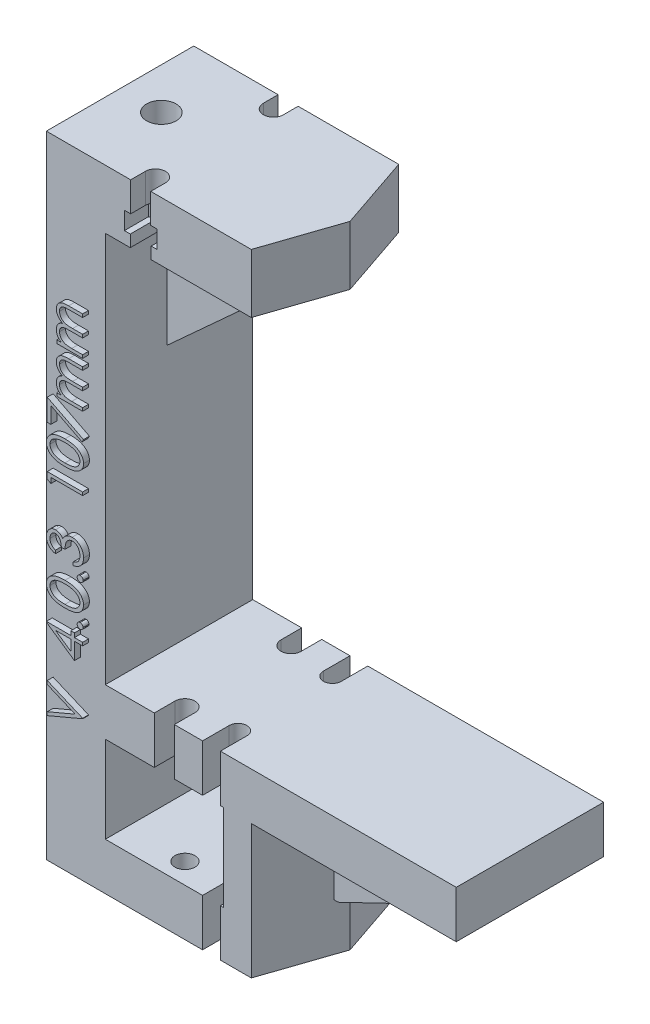
SolidWorks part; units mm, degrees
material "ABS"
ref_plane "Front" through (0, 0, 0) normal (0, 0, 1) x (1, 0, 0)
ref_plane "Top" through (0, 0, 0) normal (0, 1, 0) x (1, 0, 0)
ref_plane "Right" through (0, 0, 0) normal (1, 0, 0) x (0, 0, -1)
sketch "Sketch6" plane through (0, 0, 0) normal (0, 0, 1) x (1, 0, 0)
  line L0 (-25, 53.5) -> (15, 53.5)
  line L1 (15, 53.5) -> (15, 45.5)
  line L2 (15, 45.5) -> (-15, 45.5)
  line L3 (-15, 45.5) -> (-15, -45.5)
  line L4 (-15, -45.5) -> (25, -45.5)
  line L5 (25, -45.5) -> (25, -53.5)
  line L6 (25, -53.5) -> (-25, -53.5)
  line L7 (-25, -53.5) -> (-25, 53.5)
  line L8 (-25, 53.5) -> (25, -53.5) construction
  dimension "D1" = 107
  dimension "D2" = 8
  dimension "D4" = 50
  dimension "D5" = 40
extrude "Boss-Extrude2" add sketch "Sketch6" along normal mid plane 25
sketch "Sketch15" plane through (0, 0, 12.5) normal (0, 0, 1) x (1, 0, 0)
  line L0 (-15, -22.805) -> (15, -22.805)
  line L1 (-15, -45.5) -> (-15, 45.5) construction
  line L2 (-15, -30.805) -> (5, -30.805)
  line L3 (5, -53.5) -> (15, -53.5)
  line L4 (15, -53.5) -> (15, -22.805)
  line L5 (-25, -53.5) -> (25, -53.5) construction
  line L6 (-15, -30.805) -> (-15, -22.805)
  line L7 (5, -53.5) -> (5, -30.805)
  dimension "D2" = 8
extrude "Boss-Extrude3" add sketch "Sketch15" against normal up to surface (25 mm away) up to face at (0, 0, -12.5)
sketch "Sketch20" plane through (0, 53.5, 0) normal (0, 1, 0) x (1, 0, 0)
  line L0 (-10.7, 12.5) -> (-10.7, 10)
  line L1 (15, 12.5) -> (-25, 12.5) construction
  line L2 (-7.3, 10) -> (-7.3, 12.5)
  line L3 (-7.3, 12.5) -> (-10.7, 12.5)
  line L4 (0, 0) -> (15, 0) construction
  line L5 (15, -12.5) -> (15, 12.5) construction
  line L6 (-7.3, -12.5) -> (-10.7, -12.5)
  line L7 (-7.3, -10) -> (-7.3, -12.5)
  line L8 (-10.7, -12.5) -> (-10.7, -10)
  line L9 (-9, -10) -> (-9, 10) construction
  arc A0 (-10.7, 10) -> (-7.3, 10) centre (-9, 10) ccw
  arc A1 (-10.7, -10) -> (-7.3, -10) centre (-9, -10) cw
  dimension "D1" = 1.7
  dimension "D2" = 20
extrude "Cut-Extrude2" cut sketch "Sketch20" against normal up to next
sketch "Sketch21" plane through (0, -53.5, 0) normal (0, -1, 0) x (1, 0, 0)
  line L0 (-6.7, 12.5) -> (-6.7, 9)
  line L1 (-25, 12.5) -> (25, 12.5) construction
  line L2 (-3.3, 9) -> (-3.3, 12.5)
  line L3 (-3.3, 12.5) -> (-6.7, 12.5) construction
  line L4 (-5, -9) -> (-5, 9) construction
  line L5 (-6.7, 12.5) -> (-3.3, 12.5)
  line L7 (-3.3, -12.5) -> (-6.7, -12.5)
  line L8 (-3.3, -9) -> (-3.3, -12.5)
  line L9 (-6.7, -12.5) -> (-6.7, -9)
  arc A0 (-6.7, 9) -> (-3.3, 9) centre (-5, 9) ccw
  arc A1 (-6.7, -9) -> (-3.3, -9) centre (-5, -9) cw
  dimension "D1" = 1.7
  dimension "D2" = 18
extrude "Cut-Extrude3" cut sketch "Sketch21" against normal up to surface (30.695 mm away) up to face at (0, -22.805, 0)
sketch "Sketch22" plane through (0, 0, 0) normal (0, 0, 1) x (1, 0, 0)
  line L0 (-15, 21.805) -> (11, 45.5)
  line L1 (-7.3, 45.5) -> (15, 45.5) construction
  line L2 (-15, 45.5) -> (11, 45.5)
  line L5 (-15, -22.805) -> (-15, 45.5) construction
  line L7 (-15, 45.5) -> (-10.7, 45.5) construction
  line L8 (-15, 45.5) -> (-15, 21.805)
extrude "Boss-Extrude5" add sketch "Sketch22" along normal mid plane 4
sketch "Sketch23" plane through (0, 53.5, 0) normal (0, 1, 0) x (1, 0, 0)
  line L0 (-2.51, 12.5) -> (-2.51, 9)
  line L1 (15, 12.5) -> (-7.3, 12.5) construction
  line L2 (0.51, 9) -> (0.51, 12.5)
  line L3 (0.51, 12.5) -> (-2.51, 12.5)
  line L4 (-9, 10) -> (-1, 10) construction
  line L5 (-1, 10) -> (-1, 9) construction
  line L6 (0, 0) -> (12, 0) construction
  line L8 (0.51, -12.5) -> (-2.51, -12.5)
  line L9 (0.51, -9) -> (0.51, -12.5)
  line L10 (-2.51, -12.5) -> (-2.51, -9)
  line L11 (15, -12.5) -> (15, 12.5) construction
  arc A0 (-2.51, 9) -> (0.51, 9) centre (-1, 9) ccw
  arc A1 (-2.51, -9) -> (0.51, -9) centre (-1, -9) cw
  dimension "D1" = 1.51
  dimension "D2" = 8
  dimension "D3" = 1
  dimension "D4" = 3
extrude "Cut-Extrude4" [suppressed] cut sketch "Sketch23" against normal up to next
sketch "Sketch24" plane through (0, -53.5, 0) normal (0, -1, 0) x (1, 0, 0)
  line L0 (1.49, -12.5) -> (1.49, -8)
  line L1 (-3.3, -12.5) -> (25, -12.5) construction
  line L2 (4.51, -8) -> (4.51, -12.5)
  line L3 (4.51, -12.5) -> (1.49, -12.5)
  line L4 (3, -8) -> (3, -9) construction
  line L5 (3, -9) -> (-5, -9) construction
  line L9 (4.51, 12.5) -> (1.49, 12.5)
  line L10 (4.51, 8) -> (4.51, 12.5)
  line L11 (1.49, 12.5) -> (1.49, 8)
  arc A0 (1.49, -8) -> (4.51, -8) centre (3, -8) cw
  arc A1 (1.49, 8) -> (4.51, 8) centre (3, 8) ccw
  dimension "D2" = 8
  dimension "D3" = 1
extrude "Cut-Extrude6" cut sketch "Sketch24" against normal up to surface (30.695 mm away) up to face at (-3.3333, -22.805, 0)
sketch "Sketch28" plane through (0, 53.5, 0) normal (0, 1, 0) x (1, 0, 0)
  line L0 (-10.7, 10) -> (-7.3, 10) construction
  line L1 (-10.7, -10) -> (-7.3, -10) construction
  line L2 (-7.3, -12.5) -> (-7.3, -10) construction
  arc A0 (-10.7, 10) -> (-7.3, 10) centre (-9, 10) ccw construction
  arc A1 (-7.3, -10) -> (-10.7, -10) centre (-9, -10) ccw construction
sketch "Sketch29" plane through (-25, 0, 0) normal (-1, 0, 0) x (0, 0, 1)
  line L0 (-12.5, 53.5) -> (12.5, 53.5)
  line L1 (12.5, 53.5) -> (12.5, -53.5)
  line L2 (12.5, -53.5) -> (-12.9424, -53.5)
  line L3 (-12.9424, -53.5) -> (-12.5, 53.5)
extrude "Cut-Extrude7" [suppressed] cut sketch "Sketch29" against normal blind 6
sketch "Sketch30" plane through (0, -45.5, 0) normal (0, 1, 0) x (1, 0, 0)
  line L0 (25, 12.5) -> (25, -12.5)
  line L1 (25, -12.5) -> (15, -12.5)
  line L2 (15, -12.5) -> (15, 12.5)
  line L3 (15, 12.5) -> (25, 12.5)
extrude "Cut-Extrude8" cut sketch "Sketch30" against normal up to surface (8 mm away) up to face at (-0.8, -53.5, 0)
sketch "Sketch34" plane through (0, -22.805, 0) normal (0, 1, 0) x (1, 0, 0)
  line L1 (9.755, 12.5) -> (14, 0)
  line L2 (15, -12.5) -> (4.51, -12.5) construction
  line L3 (9.755, -12.5) -> (15, -12.5)
  line L6 (15, 12.5) -> (9.755, 12.5)
  line L7 (15, 12.5) -> (4.51, 12.5) construction
  line L9 (15, -12.5) -> (15, 12.5)
  line L10 (15, 0) -> (14, 0) construction
  line L11 (14, 0) -> (9.755, -12.5)
extrude "Cut-Extrude9" cut sketch "Sketch34" against normal through all both and the other way through all
sketch "Sketch35" plane through (0, 0, 12.5) normal (0, 0, 1) x (1, 0, 0)
  line L0 (-17.85, 53.5) -> (-17.85, -53.5) construction
  line L1 (-10.7, 53.5) -> (-25, 53.5) construction
  line L2 (-25, -53.5) -> (-6.7, -53.5) construction
  text T0 "V  4.0.3  107mm" font "Century Gothic" height 6
extrude "Boss-Extrude6" add sketch "Sketch35" along normal blind 1
sketch3d "3DSketch1"
  line L0 (4.51, -22.805, 12.5) -> (4.51, -30.805, 12.5)
  line L1 (4.51, -30.805, 12.5) -> (4.51, -30.805, -12.5)
  line L2 (4.51, -30.805, -12.5) -> (4.51, -22.805, -12.5)
  line L3 (4.51, -22.805, -12.5) -> (4.51, -22.805, 12.5)
extrude "Boss-Extrude7" add sketch "3DSketch1" along direction (1, 0, 0) on the side against the normal blind 40
sketch "Sketch37" plane through (0, 0, 0) normal (0, 0, 1) x (1, 0, 0)
  line L1 (14, -30.805) -> (44.51, -30.805)
  line L3 (5, -45.5) -> (14, -45.5) construction
  line L4 (14, -30.805) -> (14, -45.5)
  line L5 (14, -45.5) -> (44.51, -30.805)
extrude "Boss-Extrude17" add sketch "Sketch37" along direction (0, 0, 1) on the side of the normal mid plane 4 separate body
sketch "Sketch38" plane through (0, 45.5, 0) normal (0, -1, 0) x (1, 0, 0)
  line L0 (-11.75, 11.5877) -> (-11.75, 12.5) construction
  line L1 (-10.7, 10) -> (-7.3, 10) construction
  line L2 (-6.25, 8.4123) -> (-6.25, 11.5877) construction
  line L3 (-9, 6.8246) -> (-6.25, 8.4123)
  line L4 (-11.75, 8.4123) -> (-9, 6.8246)
  line L5 (-11.75, 11.5877) -> (-11.75, 8.4123) construction
  line L6 (-9, 13.1754) -> (-11.75, 11.5877) construction
  line L7 (-6.25, 11.5877) -> (-9, 13.1754) construction
  line L8 (-10.7, -10) -> (-7.3, -10) construction
  line L9 (-6.25, -11.5877) -> (-6.25, -8.4123) construction
  line L10 (-6.25, -8.4123) -> (-9, -6.8246)
  line L11 (-9, -6.8246) -> (-11.75, -8.4123)
  line L12 (-11.75, -8.4123) -> (-11.75, -11.5877) construction
  line L13 (-11.75, -11.5877) -> (-9, -13.1754) construction
  line L14 (-9, -13.1754) -> (-6.25, -11.5877) construction
  line L15 (-15, 12.5) -> (-10.7, 12.5) construction
  line L17 (-7.3, 12.5) -> (9.755, 12.5) construction
  line L18 (-6.25, 12.5) -> (-6.25, 11.5877) construction
  line L19 (-11.75, -11.5877) -> (-11.75, -12.5) construction
  line L20 (-15, -12.5) -> (-10.7, -12.5) construction
  line L21 (-11.77, -12.5) -> (-6.23, -12.5)
  line L22 (-7.3, -12.5) -> (9.755, -12.5) construction
  line L23 (-6.25, -12.5) -> (-6.25, -11.5877) construction
  line L24 (-11.77, 12.5) -> (-11.77, 8.4238)
  line L25 (-11.77, 8.4238) -> (-11.75, 8.4123)
  line L26 (-6.23, 12.5) -> (-6.23, 8.4238)
  line L27 (-6.23, 8.4238) -> (-6.25, 8.4123)
  line L28 (-11.77, 12.5) -> (-6.23, 12.5)
  line L29 (-6.25, -8.4123) -> (-6.23, -8.4238)
  line L30 (-6.23, -8.4238) -> (-6.23, -12.5)
  line L31 (-11.77, -12.5) -> (-11.77, -8.4238)
  line L32 (-11.77, -8.4238) -> (-11.75, -8.4123)
  circle A1 centre (-9, 10) radius 2.75 construction
  circle A2 centre (-9, 10) radius 3.1754 construction
  circle A3 centre (-9, -10) radius 3.1754 construction
  circle A4 centre (-9, -10) radius 2.75 construction
  point P18 (-6.25, -10)
  point P19 (-9, 10)
  point P24 (-7.625, -7.6184)
  point P25 (-10.375, -7.6184)
  point P42 (-11.75, 12.0439)
  dimension "D1" = 5.5
  dimension "D2" = 6
  dimension "D3" = 6.3509
  dimension "D4" = 5.5
  dimension "D5" = 6.3509
  dimension "D6" = 0.02
  dimension "D7" = 0.02
  dimension "D8" = 0.02
  dimension "D9" = 0.02
extrude "Cut-Extrude10" cut sketch "Sketch38" against normal blind 3
sketch "Sketch39" plane through (14, 0, 0) normal (-1, 0, 0) x (0, 0, 1)
  line L1 (-2, -45.5) -> (2, -45.5)
  line L2 (-2, -45.5) -> (-2, -30.805)
  line L3 (-2, -30.805) -> (2, -30.805)
  line L4 (2, -45.5) -> (2, -30.805)
extrude "Boss-Extrude18" add sketch "Sketch39" along normal blind 2.5
hole_wizard "Ø5.0mm Dowel Hole1" positions "Sketch41" profile "Sketch42" hole size "Ø5.0" standard "ANSI Metric"
sketch "Sketch41" plane through (0, 53.5, 0) normal (0, 1, 0) x (1, 0, 0)
  line L0 (-25, 0) -> (-18, 0) construction
  line L1 (-25, -12.5) -> (-25, 12.5) construction
  point P0 (-18, 0)
  dimension "D1" = 7
sketch "Sketch42" plane through (-18, 53.5, 0) normal (1, 0, 0) x (0, 0, 1)
  line L0 (0, 0) -> (0, 6.5022)
  line L1 (0, 6.5022) -> (2.5, 5)
  line L2 (2.5, 5) -> (2.5, 0)
  line L5 (2.5, 0) -> (0, 0)
  line L10 (0, 6.5022) -> (-2.5, 5) construction
  line L11 (0, -6.35) -> (0, 107.95) construction
  dimension "Hole Dia." = 5
  dimension "Hole Depth" = 5
  dimension "Drill Angle" = 118
sketch "Sketch43" plane through (0, 45.5, 0) normal (0, -1, 0) x (1, 0, 0)
  line L0 (-11.77, 12.5) -> (-10.77, 12.5)
  line L1 (-10.77, 12.5) -> (-10.77, 7.8465)
  line L2 (-6.23, 12.5) -> (-7.23, 12.5)
  line L3 (-7.23, 12.5) -> (-7.23, 7.8465)
  line L4 (-11.77, -12.5) -> (-10.77, -12.5)
  line L5 (-10.77, -12.5) -> (-10.77, -7.8465)
  line L6 (-6.23, -12.5) -> (-7.23, -12.5)
  line L7 (-7.23, -12.5) -> (-7.23, -7.8465)
  line L8 (5, 2) -> (5, -2)
  line L19 (-15, -12.5) -> (-11.77, -12.5)
  line L20 (-11.77, 8.4238) -> (-11.77, 12.5)
  line L21 (-11.77, -8.4238) -> (-9, -6.8246)
  line L22 (-9, -6.8246) -> (-6.23, -8.4238)
  line L23 (-11.77, 8.4238) -> (-11.77, 12.5)
  line L24 (-6.23, -12.5) -> (9.755, -12.5)
  line L25 (9.755, -12.5) -> (14, 0)
  line L26 (14, 0) -> (9.755, 12.5)
  line L27 (9.755, 12.5) -> (-6.23, 12.5)
  line L28 (-11.77, -12.5) -> (-11.77, -8.4238)
  line L29 (-6.23, 8.4238) -> (-9, 6.8246)
  line L30 (-9, 6.8246) -> (-11.77, 8.4238)
  line L31 (-11.77, -12.5) -> (-11.77, -8.4238)
  line L32 (-11.77, 12.5) -> (-15, 12.5)
  line L33 (-15, 12.5) -> (-15, 2)
  line L34 (-15, 2) -> (11, 2)
  line L35 (11, 2) -> (11, -2)
  line L36 (11, -2) -> (-15, -2)
  line L37 (-15, -2) -> (-15, -12.5)
  line L38 (-15, -12.5) -> (-11.77, -12.5)
  line L40 (-11.77, -8.4238) -> (-9, -6.8246)
  line L41 (-9, -6.8246) -> (-6.23, -8.4238)
  line L43 (-6.23, -12.5) -> (9.755, -12.5)
  line L44 (9.755, -12.5) -> (14, 0)
  line L45 (14, 0) -> (9.755, 12.5)
  line L46 (9.755, 12.5) -> (-6.23, 12.5)
  line L48 (-6.23, 8.4238) -> (-9, 6.8246)
  line L49 (-9, 6.8246) -> (-11.77, 8.4238)
  line L51 (-11.77, 12.5) -> (-15, 12.5)
  line L52 (-15, 12.5) -> (-15, 2)
  line L53 (-15, 2) -> (11, 2)
  line L54 (11, 2) -> (11, -2)
  line L55 (11, -2) -> (-15, -2)
  line L56 (-15, -2) -> (-15, -12.5)
  line L57 (-6.23, -8.4238) -> (-6.23, -12.5)
  line L58 (-6.23, -8.4238) -> (-6.23, -12.5)
  line L59 (-6.23, 12.5) -> (-6.23, 8.4238)
  line L60 (-6.23, 12.5) -> (-6.23, 8.4238)
  line M22 (-11.77, -8.4238) -> (-9, -6.8246)
  line M23 (-9, -6.8246) -> (-6.23, -8.4238)
  line M30 (-6.23, 8.4238) -> (-9, 6.8246)
  line M31 (-9, 6.8246) -> (-11.77, 8.4238)
  line M35 (-15, 2) -> (11, 2)
  line M36 (11, 2) -> (11, -2)
  line M37 (11, -2) -> (-15, -2)
  line M39 (-11.77, 8.4238) -> (-11.77, 12.5)
  line M40 (-11.77, -12.5) -> (-11.77, -8.4238)
  line M41 (-6.23, -8.4238) -> (-6.23, -12.5)
  line M42 (-6.23, 12.5) -> (-6.23, 8.4238)
  dimension "D2" = 1
  dimension "D3" = 1
  dimension "D4" = 1
  dimension "D5" = 1
  dimension "D6" = 6
  dimension "D1" = 0
extrude "Boss-Extrude19" add sketch "Sketch43" along normal blind 2 contours L8 M35 M37 M36 | L1 L0 M39 M31 | L2 L3 M30 M42 | L4 L5 M22 M40 | L7 L6 M41 M23 | L38 L31 L40 L41 L58 L43 L44 L45 L46 L60 L48 L49 L23 L51 L52 L53 L54 L55 L56
sketch "Sketch44" plane through (0, -53.5, 0) normal (0, -1, 0) x (1, 0, 0)
  line L0 (-6.7, -9) -> (-6.7, -12.5)
  line L1 (-6.7, -12.5) -> (-3.3, -12.5)
  line L2 (-3.3, -12.5) -> (-3.3, -9)
  line L3 (-6.7, 9) -> (-6.7, 12.5)
  line L4 (-6.7, 12.5) -> (-3.3, 12.5)
  line L5 (-3.3, 12.5) -> (-3.3, 9)
  circle A0 centre (-5, -9) radius 1.7
  circle A1 centre (-5, 9) radius 1.7
  line M8 (-3.3, 12.5) -> (-3.3, 9)
  line M10 (-6.7, 9) -> (-6.7, 12.5)
  line M14 (-6.7, -12.5) -> (-6.7, -9)
  line M16 (-3.3, -9) -> (-3.3, -12.5)
extrude "Boss-Extrude20" add sketch "Sketch44" against normal up to surface (8 mm away) contours A1 L4 M8 M10 | A0 L1 M14 M16
